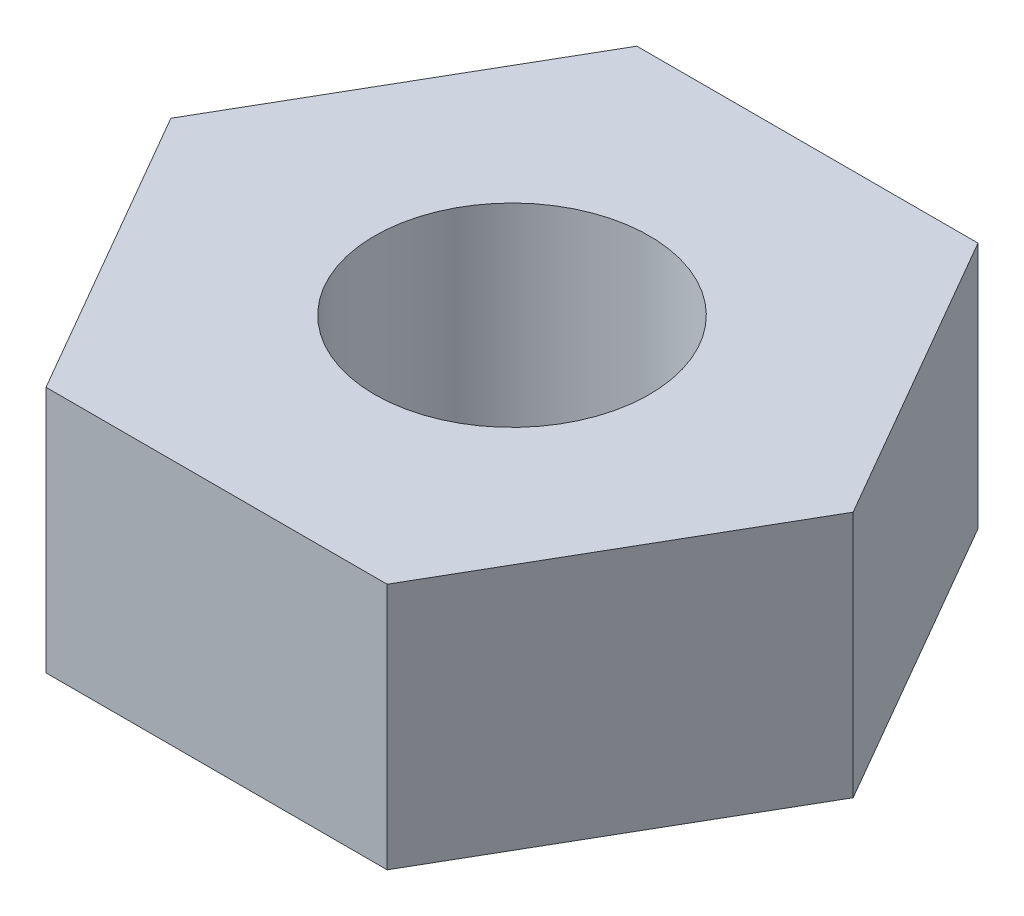
SolidWorks part; units mm, degrees
ref_plane "Front Plane" through (0, 0, 0) normal (0, 0, 1) x (1, 0, 0)
ref_plane "Top Plane" through (0, 0, 0) normal (0, 1, 0) x (1, 0, 0)
ref_plane "Right Plane" through (0, 0, 0) normal (1, 0, 0) x (0, 0, -1)
sketch "Sketch1" plane through (0, 0, 0) normal (0, 1, 0) x (1, 0, 0)
  line L1 (4.9652, 0) -> (2.4826, 4.3)
  line L2 (2.4826, 4.3) -> (-2.4826, 4.3)
  line L3 (-2.4826, 4.3) -> (-4.9652, 0)
  line L4 (-4.9652, 0) -> (-2.4826, -4.3)
  line L5 (-2.4826, -4.3) -> (2.4826, -4.3)
  line L6 (2.4826, -4.3) -> (4.9652, 0)
  circle A0 centre (0, 0) radius 4.3 construction
  circle A1 centre (0, 0) radius 2
  dimension "D1" = 8.6
  dimension "D2" = 4
extrude "Boss-Extrude1" add sketch "Sketch1" along normal blind 3.6
